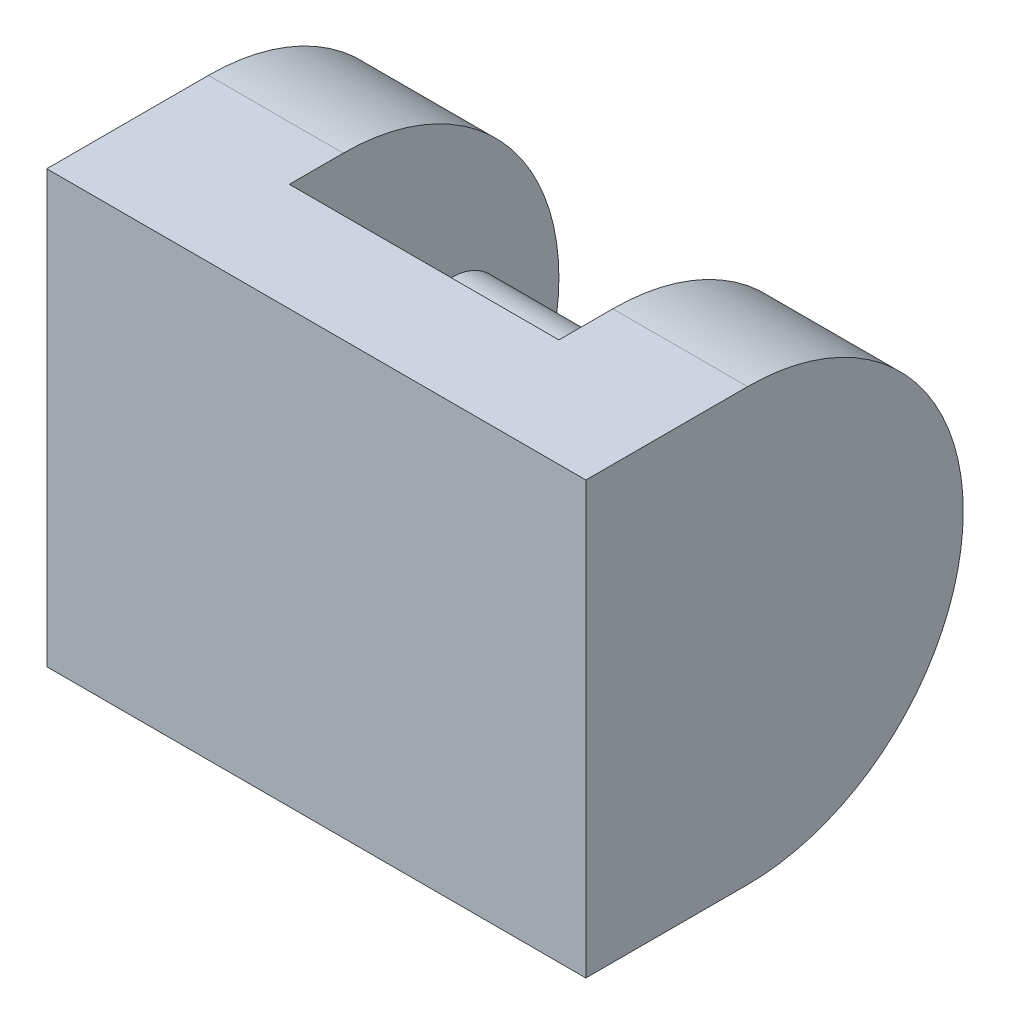
SolidWorks part; units mm, degrees
ref_plane "前视基准面" through (0, 0, 0) normal (0, 0, 1) x (1, 0, 0)
ref_plane "上视基准面" through (0, 0, 0) normal (0, 1, 0) x (1, 0, 0)
ref_plane "右视基准面" through (0, 0, 0) normal (1, 0, 0) x (0, 0, -1)
sketch "草图1" plane through (0, 0, 0) normal (0, 0, 1) x (1, 0, 0)
  line L1 (-5, -4) -> (5, -4)
  line L2 (-5, -4) -> (-5, 4)
  line L3 (-5, 4) -> (5, 4)
  line L4 (5, -4) -> (5, 4)
  line L5 (-5, -4) -> (5, 4) construction
  line L6 (-5, 4) -> (5, -4) construction
  point P0 (0, 0)
  dimension "D1" = 10
  dimension "D2" = 8
extrude "凸台-拉伸1" add sketch "草图1" along normal blind 3
sketch "草图3" plane through (5, 0, 0) normal (1, 0, 0) x (0, 0, -1)
  line L0 (0, 4) -> (0, -4)
  circle A0 centre (0, 0) radius 4
  line M2 (0, -4) -> (0, 4)
extrude "凸台-拉伸2" add sketch "草图3" against normal blind 10 contours A0 M2
sketch "草图4" plane through (0, 0, 0) normal (0, 0, 1) x (1, 0, 0)
  line L0 (5, 4) -> (-5, 4) construction
  line L1 (-2.5, -4) -> (2.5, -4)
  line L2 (-2.5, -4) -> (-2.5, 4)
  line L3 (-2.5, 4) -> (2.5, 4)
  line L4 (2.5, -4) -> (2.5, 4)
  line L5 (-2.5, -4) -> (2.5, 4) construction
  line L6 (-2.5, 4) -> (2.5, -4) construction
  point P0 (0, 0)
  dimension "D1" = 5
extrude "切除-拉伸1" cut sketch "草图4" against normal blind 10
sketch "草图5" plane through (-5, 0, 0) normal (-1, 0, 0) x (0, 0, 1)
  circle A0 centre (-2, 0) radius 1
  dimension "D1" = 2
  dimension "D2" = 2
extrude "凸台-拉伸3" add sketch "草图5" against normal blind 10
sketch "草图7" plane through (0, -4, 0) normal (0, -1, 0) x (-1, 0, 0)
  line L0 (2.5, 0) -> (2.5, -1)
  line L1 (2.5, -1) -> (-2.5, -1)
  line L2 (-2.5, -1) -> (-2.5, 0)
  line L3 (-2.5, 0) -> (2.5, 0)
  dimension "D1" = 1
extrude "切除-拉伸2" cut sketch "草图7" against normal blind 10
